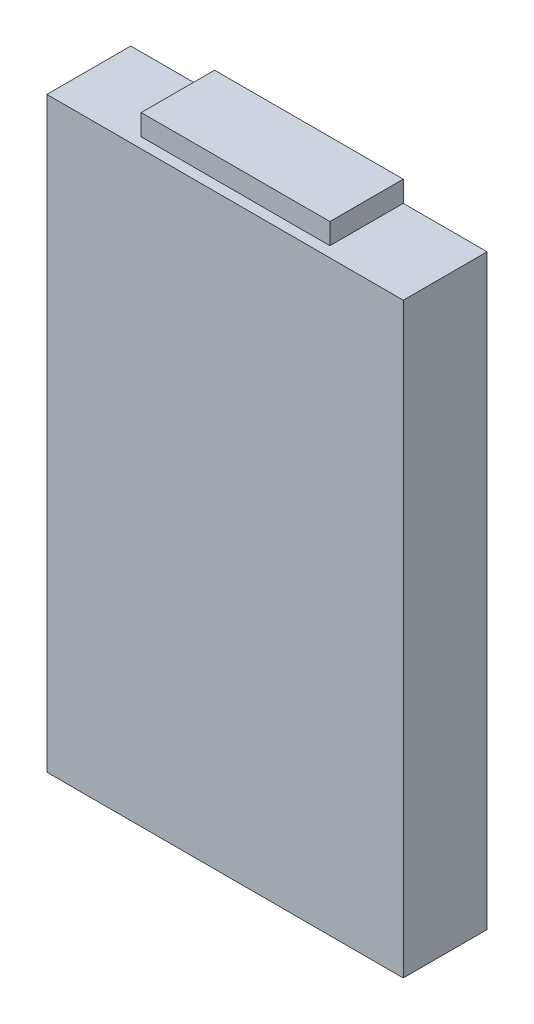
SolidWorks part; units mm, degrees
ref_plane "Front Plane" through (0, 0, 0) normal (0, 0, 1) x (1, 0, 0)
ref_plane "Top Plane" through (0, 0, 0) normal (0, 1, 0) x (1, 0, 0)
ref_plane "Right Plane" through (0, 0, 0) normal (1, 0, 0) x (0, 0, -1)
sketch "Sketch1" plane through (0, 0, 0) normal (0, 0, 1) x (1, 0, 0)
  line L1 (0, 0) -> (17, 0)
  line L2 (0, 0) -> (0, 28)
  line L3 (0, 28) -> (17, 28)
  line L4 (17, 0) -> (17, 28)
  dimension "D1" = 17
  dimension "D2" = 28
extrude "Boss-Extrude1" add sketch "Sketch1" along normal blind 4
sketch "Sketch2" plane through (0, 28, 0) normal (0, 1, 0) x (1, 0, 0)
  line L0 (17, 0) -> (0, 0) construction
  line L1 (4, 0) -> (13, 0)
  line L2 (4, 0) -> (4, -3.5)
  line L3 (4, -3.5) -> (13, -3.5)
  line L4 (13, 0) -> (13, -3.5)
  point P6 (8.5, 0)
  dimension "D1" = 3.5
  dimension "D2" = 9
extrude "Boss-Extrude2" add sketch "Sketch2" along normal blind 1
